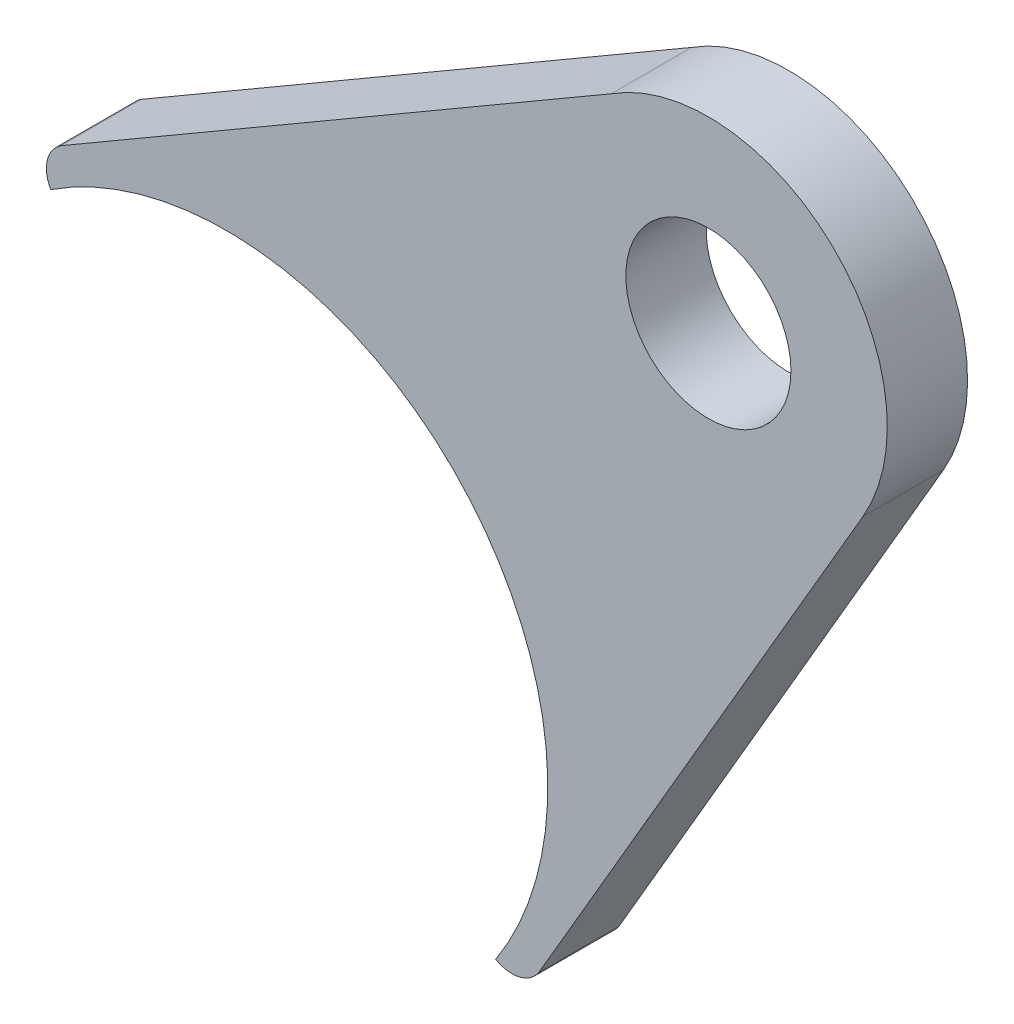
SolidWorks part; units mm, degrees
ref_plane "Front Plane" through (0, 0, 0) normal (0, 0, 1) x (1, 0, 0)
ref_plane "Top Plane" through (0, 0, 0) normal (0, 1, 0) x (1, 0, 0)
ref_plane "Right Plane" through (0, 0, 0) normal (1, 0, 0) x (0, 0, -1)
sketch "Sketch1" plane through (0, 0, 0) normal (0, 0, 1) x (1, 0, 0)
  line L4 (-6.5491, 12.3333) -> (15.2029, 24.9863)
  line L5 (12.3489, -6.5253) -> (25.1637, 15.4915)
  arc A0 (10.6407, -6.9329) -> (-6.9547, 10.6265) centre (0, 0) ccw
  circle A1 centre (19.05, 19.05) radius 3.2639
  arc A3 (10.6407, -6.9329) -> (12.3489, -6.5253) centre (11.2818, -5.8366) ccw
  arc A4 (25.1637, 15.4915) -> (15.2029, 24.9863) centre (19.05, 19.05) ccw
  arc A5 (-6.9547, 10.6265) -> (-6.5491, 12.3333) centre (-5.8584, 11.2675) cw
  dimension "D1" = 25.4
  dimension "D2" = 6.5278
  dimension "D5" = 14.1478
  dimension "D6" = 1.27
  dimension "D7" = 1.27
  dimension "D3" = 19.05
  dimension "D4" = 19.05
extrude "Boss-Extrude1" add sketch "Sketch1" along normal blind 3.175
ref_point "Point2"
